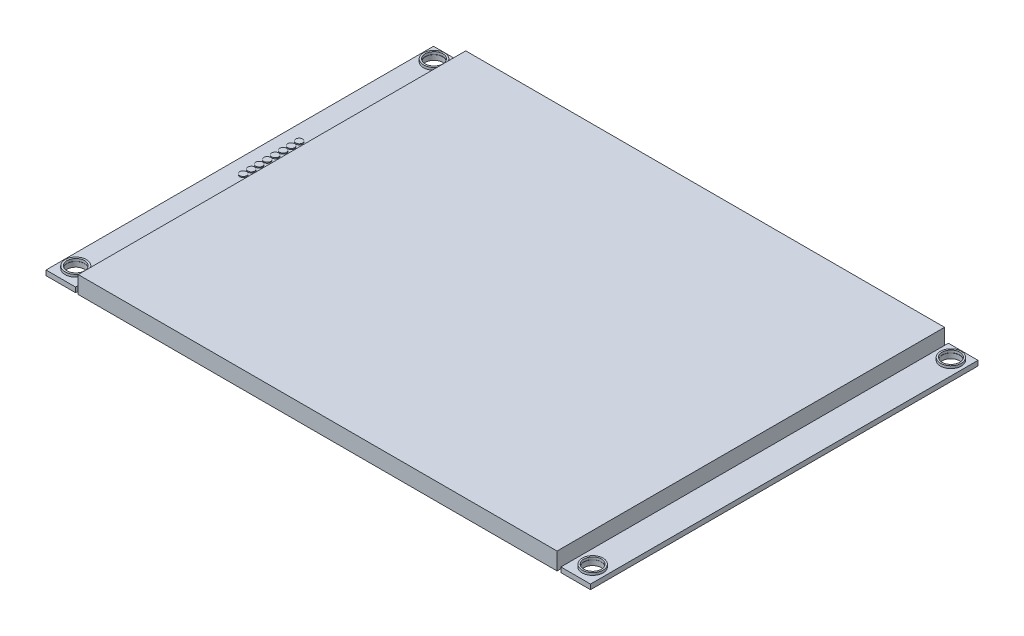
SolidWorks part; units mm, degrees
ref_plane "Front Plane" through (0, 0, 0) normal (0, 0, 1) x (1, 0, 0)
ref_plane "Top Plane" through (0, 0, 0) normal (0, 1, 0) x (1, 0, 0)
ref_plane "Right Plane" through (0, 0, 0) normal (1, 0, 0) x (0, 0, -1)
sketch "Sketch8" plane through (-0.3234, 0, 0) normal (0, 1, 0) x (1, 0, 0)
  line L1 (-93.3958, 59.4838) -> (-87.3958, 59.4838)
  line L2 (-93.3958, 59.4838) -> (-93.3958, -19.0162)
  line L3 (-93.3958, -19.0162) -> (-87.3958, -19.0162)
  line L4 (-87.3958, 59.4838) -> (-87.3958, -19.0162)
  line L5 (10.8515, 59.5365) -> (16.8515, 59.5365)
  line L6 (10.8515, 59.5365) -> (10.8515, -18.9635)
  line L7 (10.8515, -18.9635) -> (16.8515, -18.9635)
  line L8 (16.8515, 59.5365) -> (16.8515, -18.9635)
  dimension "D1" = 6
  dimension "D2" = 78.5
  dimension "D3" = 78.5
  dimension "D4" = 6
extrude "Boss-Extrude8" add sketch "Sketch8" along normal blind 1 contours L8 L7 L6 L5 | L2 L3 L4 L1
sketch "Sketch9" plane through (0, 0, 0) normal (0, 1, 0) x (1, 0, 0)
  line L1 (-87.1525, 59.4425) -> (9.8475, 59.4425)
  line L2 (-87.1525, 59.4425) -> (-87.1525, -19.0575)
  line L3 (-87.1525, -19.0575) -> (9.8475, -19.0575)
  line L4 (9.8475, 59.4425) -> (9.8475, -19.0575)
  dimension "D1" = 97
  dimension "D2" = 78.5
extrude "Boss-Extrude9" add sketch "Sketch9" along normal blind 3.5 separate body
sketch "Sketch11" plane through (0, 1, 0) normal (0, 1, 0) x (1, 0, 0)
  circle A0 centre (-90.9566, 56.8237) radius 1.75
  circle A1 centre (-90.9566, 56.8237) radius 1.75
  circle A2 centre (-90.9566, -17.4981) radius 0.347
  circle A3 centre (-90.9566, -15.7481) radius 1.75
  circle A4 centre (13.7443, 56.8237) radius 1.75
  circle A5 centre (13.7443, -15.7481) radius 1.75
  point P11 (13.7443, 56.8237)
  point P12 (-90.9566, 56.8237)
  point P13 (13.7443, -15.7481)
  point P14 (0, 0)
  point P15 (0, 0)
  point P16 (0, 0)
extrude "Cut-Extrude1" cut sketch "Sketch11" against normal through all contours A0 | A3 | A5 | A4
sketch "Sketch12" plane through (0, 1, 0) normal (0, 1, 0) x (1, 0, 0)
  circle A2 centre (-90.5037, 27.4288) radius 0.7
  circle A3 centre (-90.5037, 25.8087) radius 0.7
  circle A4 centre (-90.5037, 24.1886) radius 0.7
  circle A5 centre (-90.5037, 22.605) radius 0.7
  circle A6 centre (-90.5037, 20.9506) radius 0.7
  circle A7 centre (-90.4383, 19.2952) radius 0.7
  circle A8 centre (-90.4383, 17.6598) radius 0.7
  circle A9 centre (-90.5037, 29.0628) radius 0.7
extrude "Boss-Extrude10" add sketch "Sketch12" along normal blind 0.2
sketch "Sketch13" plane through (0, 1, 0) normal (0, 1, 0) x (1, 0, 0)
  circle A0 centre (-90.9566, 56.8237) radius 2.124
  circle A1 centre (-90.9566, -15.7481) radius 2.1549
  circle A2 centre (13.7443, 56.8237) radius 2.11
  circle A3 centre (13.7443, -15.7481) radius 2.11
extrude "Boss-Extrude11" add sketch "Sketch13" along normal blind 0.5
sketch "Sketch14" plane through (0, 1, 0) normal (0, 1, 0) x (1, 0, 0)
  circle A0 centre (-90.9627, 56.835) radius 1.785
  circle A1 centre (-90.9566, -15.7481) radius 1.785
  circle A2 centre (13.7443, -15.7481) radius 1.785
  circle A3 centre (13.7443, 56.835) radius 1.785
  point P10 (0, 0)
extrude "Cut-Extrude3" cut sketch "Sketch14" along normal through all
